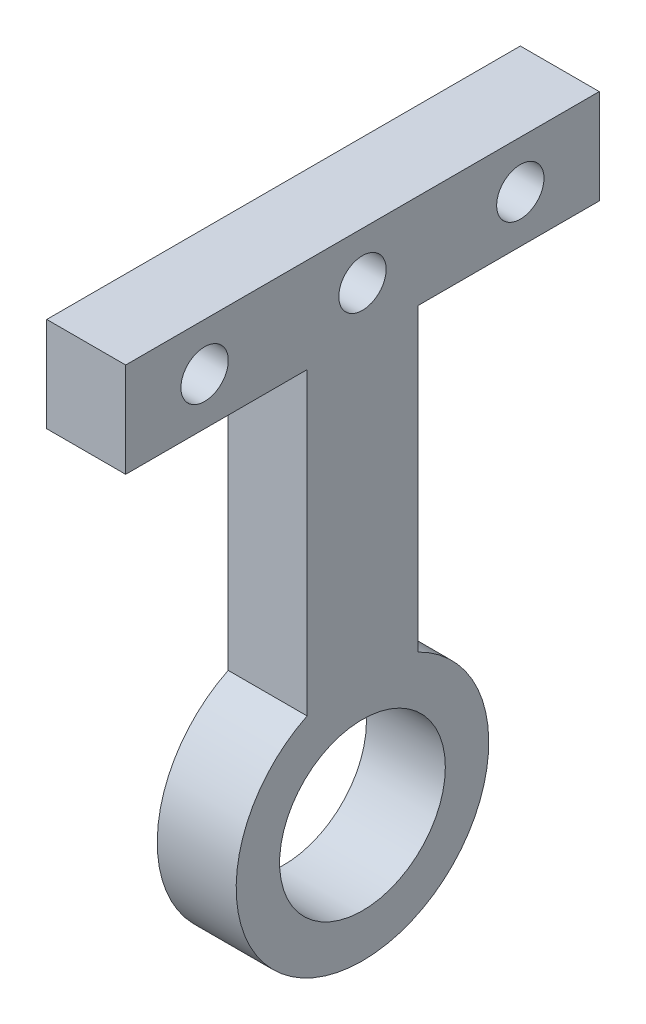
SolidWorks part; units mm, degrees
ref_plane "前视基准面" through (0, 0, 0) normal (0, 0, 1) x (1, 0, 0)
ref_plane "上视基准面" through (0, 0, 0) normal (0, 1, 0) x (1, 0, 0)
ref_plane "右视基准面" through (0, 0, 0) normal (1, 0, 0) x (0, 0, -1)
other "Configuration Table"
sketch "草图1" plane through (0, 0, 0) normal (1, 0, 0) x (0, 0, -1)
  line L2 (3.5065, 7.1906) -> (3.5065, 32.1906)
  line L3 (3.5065, 32.1906) -> (-3.5065, 32.1906)
  line L4 (-3.5065, 7.1906) -> (-3.5065, 32.1906)
  arc A0 (-3.5065, 7.1906) -> (3.5065, 7.1906) centre (0, 0) ccw
  dimension "D1" = 16
  dimension "D2" = 25
extrude "凸台-拉伸1" add sketch "草图1" along normal blind 5
sketch "草图4" plane through (0, 0, 0) normal (1, 0, 0) x (0, 0, -1)
  line L0 (175.4319, 180.3434) -> (722.0985, 180.3434) construction
  line L1 (75.4826, -0.5829) -> (97.737, -0.5829)
  line L2 (90.7235, 3.9579) -> (93.6884, 19.6808)
  line L3 (85.2757, 13.1262) -> (92.2059, 11.8194)
  dimension "D1" = 22.2544
  dimension "D2" = 16
sketch "草图5" plane through (5, 0, 0) normal (1, 0, 0) x (0, 0, -1)
  circle A0 centre (0, 0) radius 5.25
  dimension "D1" = 10.5
extrude "切除-拉伸1" cut sketch "草图5" against normal blind 5
sketch "草图9" plane through (5, 0, 0) normal (1, 0, 0) x (0, 0, -1)
  line L0 (-3.5065, 32.1906) -> (15, 32.1906)
  line L1 (15, 32.1906) -> (15, 26.1906)
  line L2 (15, 26.1906) -> (-15, 26.1906)
  line L3 (-15, 26.1906) -> (-15, 32.1906)
  line L4 (-15, 32.1906) -> (-3.5065, 32.1906)
  line L7 (3.5065, 32.1906) -> (-3.5065, 32.1906) construction
  point P8 (0, 32.1906)
  point P9 (0, 26.1906)
  dimension "D1" = 30
  dimension "D2" = 6
extrude "凸台-拉伸3" add sketch "草图9" against normal blind 5
sketch "草图10" plane through (0, 0, 0) normal (-1, 0, 0) x (0, 0, 1)
  line L0 (0, 32.1906) -> (0, 33.9441) construction
  line L1 (-15, 32.1906) -> (15, 32.1906) construction
  line L2 (-3.5065, 26.1906) -> (0, 26.1906) construction
  circle A6 centre (0, 29.1906) radius 1.5
  circle A7 centre (-10, 29.1906) radius 1.5
  circle A8 centre (10, 29.1906) radius 1.5
  dimension "D1" = 3
  dimension "D2" = 3
  dimension "D3" = 3
  dimension "D4" = 10
  dimension "D5" = 10
  dimension "D6" = 3
extrude "切除-拉伸2" cut sketch "草图10" against normal through all
sketch "草图7" plane through (5, 0, 0) normal (1, 0, 0) x (0, 0, -1)
  line L0 (-20, 40) -> (20, 40) construction
  line L3 (-20, 44) -> (20, 44)
  line L4 (-20, 36) -> (20, 36)
  line L5 (-3.5065, 16.6906) -> (3.5065, 16.6906) construction
  line L6 (-3.5065, 26.1906) -> (-3.5065, 7.1906) construction
  line L7 (3.5065, 7.1906) -> (3.5065, 26.1906) construction
  arc A0 (-20, 44) -> (-20, 36) centre (-20, 40) ccw
  arc A1 (20, 36) -> (20, 44) centre (20, 40) ccw
  circle A2 centre (-20, 40) radius 2
  circle A3 centre (20, 40) radius 2
  point P2 (0, 16.6906)
  point P6 (0, 40)
  dimension "D3" = 4
  dimension "D4" = 4
  dimension "D5" = 4
  dimension "D1" = 40
  dimension "D2" = 40
